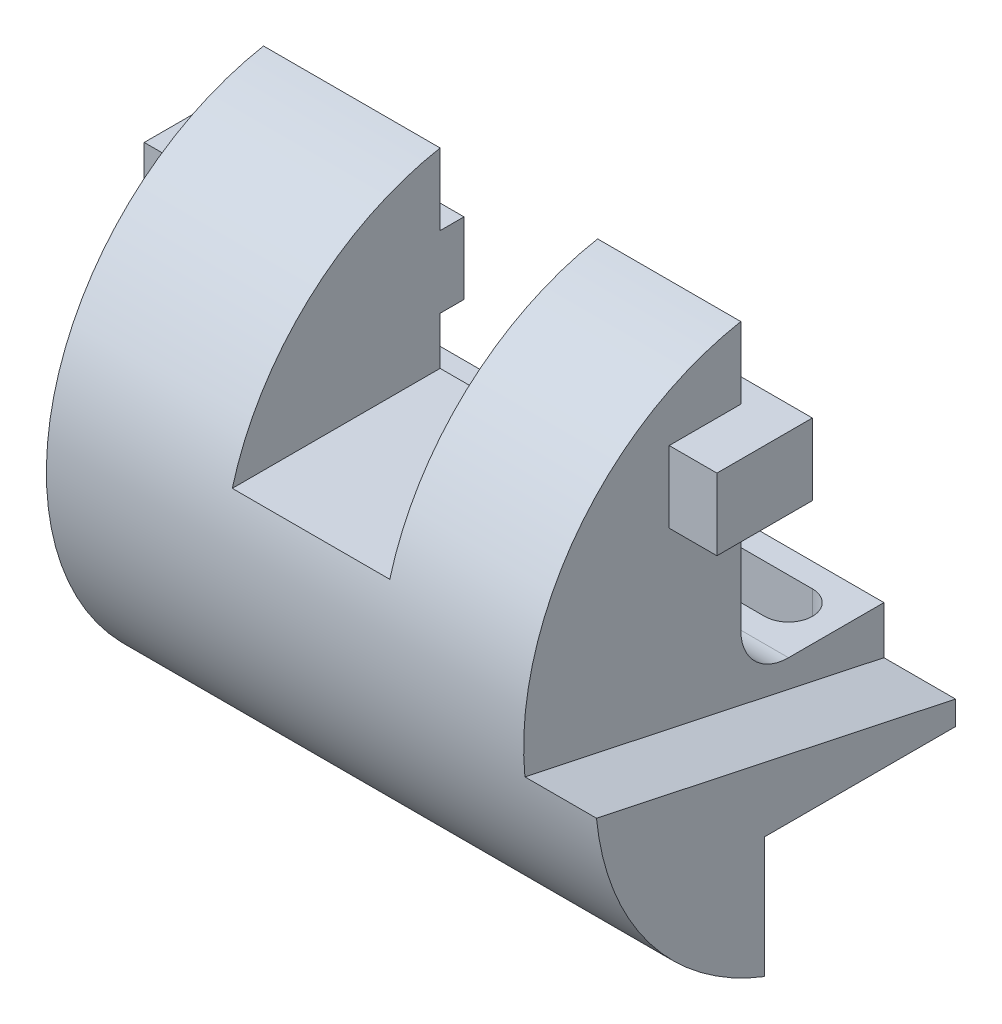
SolidWorks part; units mm, degrees
material "1060 Alloy"
ref_plane "Front Plane" through (0, 0, 0) normal (0, 0, 1) x (1, 0, 0)
ref_plane "Top Plane" through (0, 0, 0) normal (0, 1, 0) x (1, 0, 0)
ref_plane "Right Plane" through (0, 0, 0) normal (1, 0, 0) x (0, 0, -1)
sketch "Sketch1" plane through (0, 0, 0) normal (1, 0, 0) x (0, 0, -1)
  line L0 (0, 0) -> (0, -15)
  line L1 (0, -15) -> (-40, -15)
  line L2 (-40, -15) -> (-40, -40.3628)
  line L3 (0, 0) -> (-20, 0)
  line L4 (-30, 10) -> (-30, 66)
  arc A0 (-40, -40.3628) -> (-30, 66) centre (-20, 11.4083) cw
  arc A2 (-30, 10) -> (-20, 0) centre (-20, 10) ccw
  point P6 (0, 0)
  point P8 (-40, -41.3449)
  point P9 (0, 0)
  point P14 (0, 0)
  dimension "D3" = 55.5
  dimension "D4" = 10
  dimension "D1" = 15
  dimension "D2" = 40
  dimension "D5" = 10
  dimension "D6" = 20
  dimension "D7" = 66
extrude "Boss-Extrude1" add sketch "Sketch1" along normal blind 115
sketch "Sketch2" plane through (115, 0, 0) normal (1, 0, 0) x (0, 0, -1)
  line L0 (0, -10) -> (-75.235, 5.9917)
  line L1 (0, -15) -> (0, 0) construction
  arc A0 (-30, 66) -> (-40, -40.3628) centre (-20, 11.4083) ccw construction
  dimension "D1" = 5
  dimension "D2" = 78
extrude "Cut-Extrude1" cut sketch "Sketch2" against normal blind 15 and the other way through all
sketch "Sketch3" plane through (0, 0, 0) normal (-1, 0, 0) x (0, 0, 1)
  line L0 (30, 10) -> (30, 66) construction
  line L1 (25, 51) -> (45, 51)
  line L2 (25, 51) -> (25, 36)
  line L3 (25, 36) -> (45, 36)
  line L4 (45, 51) -> (45, 36)
  line L5 (25, 51) -> (45, 36) construction
  line L6 (25, 36) -> (45, 51) construction
  point P0 (35, 43.5)
  dimension "D1" = 20
  dimension "D2" = 15
  dimension "D3" = 15
  dimension "D4" = 5
extrude "Boss-Extrude2" add sketch "Sketch3" along normal blind 10 and the other way blind 110
sketch "Sketch4" plane through (0, 0, 0) normal (0, 1, 0) x (1, 0, 0)
  line L0 (10, -10) -> (90, -10) construction
  line L1 (10, -5) -> (90, -5)
  line L2 (10, -15) -> (90, -15)
  line L3 (100, 0) -> (0, 0) construction
  line L4 (0, 0) -> (0, -20) construction
  arc A0 (10, -5) -> (10, -15) centre (10, -10) ccw
  arc A1 (90, -15) -> (90, -5) centre (90, -10) ccw
  point P2 (50, -10)
  point P9 (0, 0)
  point P11 (7.345, -8.9767)
  dimension "D1" = 10
  dimension "D2" = 10
  dimension "D3" = 80
  dimension "D4" = 10
extrude "Cut-Extrude2" cut sketch "Sketch4" against normal through all
sketch "Sketch5" plane through (0, 0, 25) normal (0, 0, -1) x (-1, 0, 0)
  line L0 (-100, 66) -> (0, 66) construction
  line L1 (-70, 66) -> (-37, 66)
  line L2 (-70, 66) -> (-70, 26)
  line L3 (-70, 26) -> (-37, 26)
  line L4 (-37, 66) -> (-37, 26)
  line L5 (-100, 51) -> (-100, 66) construction
  line L6 (-110, 36) -> (10, 36) construction
  dimension "D1" = 30
  dimension "D2" = 33
  dimension "D3" = 10
extrude "Cut-Extrude3" cut sketch "Sketch5" against normal through all
